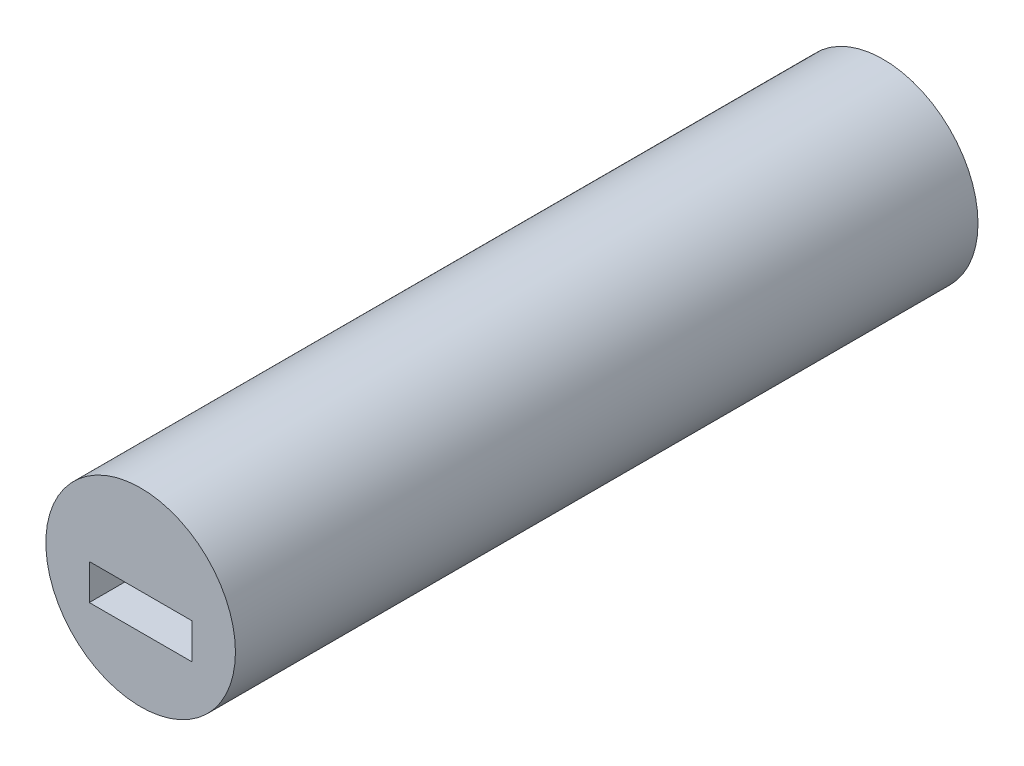
SolidWorks part; units mm, degrees
ref_plane "Alzado" through (0, 0, 0) normal (0, 0, 1) x (1, 0, 0)
ref_plane "Planta" through (0, 0, 0) normal (0, 1, 0) x (1, 0, 0)
ref_plane "Vista lateral" through (0, 0, 0) normal (1, 0, 0) x (0, 0, -1)
sketch "Croquis1" plane through (0, 0, 0) normal (0, 0, 1) x (1, 0, 0)
  circle A0 centre (0, 0) radius 12
  dimension "D1" = 24
extrude "Saliente-Extruir1" add sketch "Croquis1" along normal blind 69
sketch "Croquis2" plane through (0, 0, 69) normal (0, 0, 1) x (1, 0, 0)
  line L0 (0, 0) -> (0, -1.5656) construction
  line L1 (-6.5, 0.6844) -> (6.5, 0.6844)
  line L2 (-6.5, 0.6844) -> (-6.5, -3.8156)
  line L3 (-6.5, -3.8156) -> (6.5, -3.8156)
  line L4 (6.5, 0.6844) -> (6.5, -3.8156)
  line L5 (-6.5, 0.6844) -> (6.5, -3.8156) construction
  line L6 (-6.5, -3.8156) -> (6.5, 0.6844) construction
  circle A0 centre (0, 0) radius 12
  circle A1 centre (0, 0) radius 12 construction
  point P5 (0, -1.5656)
  point P10 (0, -1.5656)
  dimension "D1" = 4.5
  dimension "D2" = 13
extrude "Saliente-Extruir2" add sketch "Croquis2" along normal blind 25
